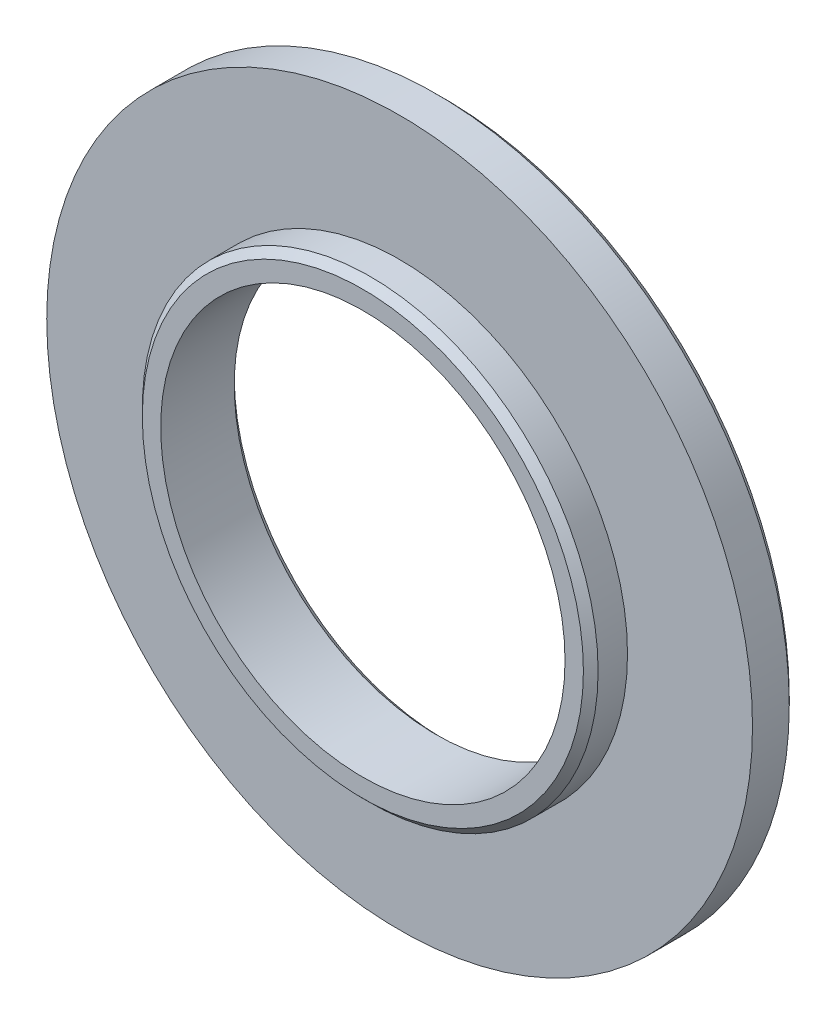
SolidWorks part; units mm, degrees
ref_plane "Piano frontale" through (0, 0, 0) normal (0, 0, 1) x (1, 0, 0)
ref_plane "Piano superiore" through (0, 0, 0) normal (0, 1, 0) x (1, 0, 0)
ref_plane "Piano destro" through (0, 0, 0) normal (1, 0, 0) x (0, 0, -1)
sketch "Schizzo1" plane through (0, 0, 0) normal (0, 0, 1) x (1, 0, 0)
  circle A0 centre (0, 0) radius 48
  dimension "D1" = 96
extrude "Estrusione1" add sketch "Schizzo1" along normal blind 6
sketch "Schizzo2" plane through (0, 0, 6) normal (0, 0, 1) x (1, 0, 0)
  circle A0 centre (0, 0) radius 31
  dimension "D1" = 62
extrude "Estrusione2" add sketch "Schizzo2" along normal blind 5
chamfer "Smusso1" distance 1 angle 45 2 edges at (48, 0, 0) (31, 0, 11)
sketch "Schizzo3" plane through (0, 0, 11) normal (0, 0, 1) x (1, 0, 0)
  circle A0 centre (0, 0) radius 27.5
  dimension "D1" = 55
extrude "Estrusione3" cut sketch "Schizzo3" against normal through all
chamfer "Smusso2" distance 1 angle 45 1 edges at (27.5, 0, 0)
